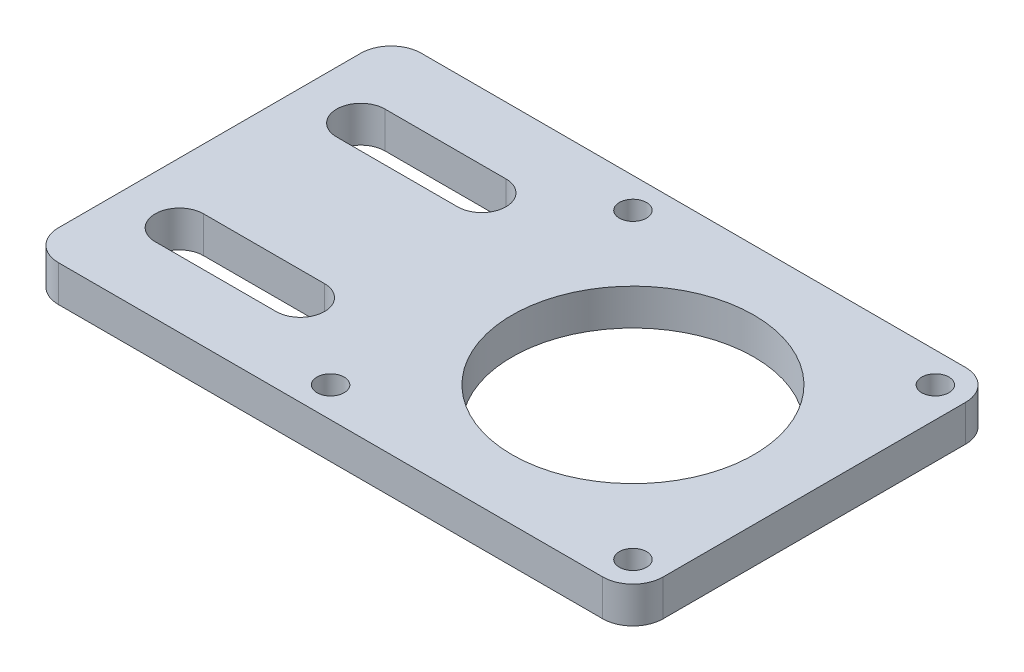
SolidWorks part; units mm, degrees
ref_plane "Front Plane" through (0, 0, 0) normal (0, 0, 1) x (1, 0, 0)
ref_plane "Top Plane" through (0, 0, 0) normal (0, 1, 0) x (1, 0, 0)
ref_plane "Right Plane" through (0, 0, 0) normal (1, 0, 0) x (0, 0, -1)
sketch "Sketch1" plane through (0, 0, 0) normal (0, 1, 0) x (1, 0, 0)
  line L0 (0, -25) -> (0, 25)
  line L1 (0, -55) -> (0, 55) construction
  line L2 (5, 30) -> (95, 30)
  line L3 (100, 25) -> (100, -25)
  line L4 (-55, 0) -> (55, 0) construction
  line L5 (5, -30) -> (95, -30)
  line L6 (10, 15) -> (30, 15) construction
  line L7 (10, 19) -> (30, 19)
  line L8 (10, 11) -> (30, 11)
  line L9 (10, -15) -> (30, -15) construction
  line L10 (10, -19) -> (30, -19)
  line L11 (10, -11) -> (30, -11)
  line L12 (45, 25) -> (95, -25) construction
  arc A0 (0, -25) -> (5, -30) centre (5, -25) ccw
  arc A1 (95, -30) -> (100, -25) centre (95, -25) ccw
  arc A2 (95, 30) -> (100, 25) centre (95, 25) cw
  arc A3 (5, 30) -> (0, 25) centre (5, 25) ccw
  circle A4 centre (95, 25) radius 2.25
  circle A5 centre (45, 25) radius 2.25
  circle A6 centre (45, -25) radius 2.25
  circle A7 centre (95, -25) radius 2.25
  arc A8 (10, 19) -> (10, 11) centre (10, 15) ccw
  arc A9 (30, 11) -> (30, 19) centre (30, 15) ccw
  arc A10 (10, -19) -> (10, -11) centre (10, -15) cw
  arc A11 (30, -11) -> (30, -19) centre (30, -15) cw
  circle A12 centre (70, 0) radius 20
  point P10 (100, 0)
  point P11 (0, 0)
  point P13 (0, -30)
  point P16 (100, -30)
  point P19 (100, 30)
  point P22 (0, 30)
  point P33 (20, 15)
  point P43 (20, -15)
  dimension "D3" = 5
  dimension "D6" = 4.5
  dimension "D12" = 40
  dimension "D1" = 100
  dimension "D2" = 60
  dimension "D4" = 50
  dimension "D5" = 50
  dimension "D7" = 5
  dimension "D8" = 8
  dimension "D9" = 20
  dimension "D10" = 10
  dimension "D11" = 30
extrude "Boss-Extrude1" add sketch "Sketch1" along normal blind 6
